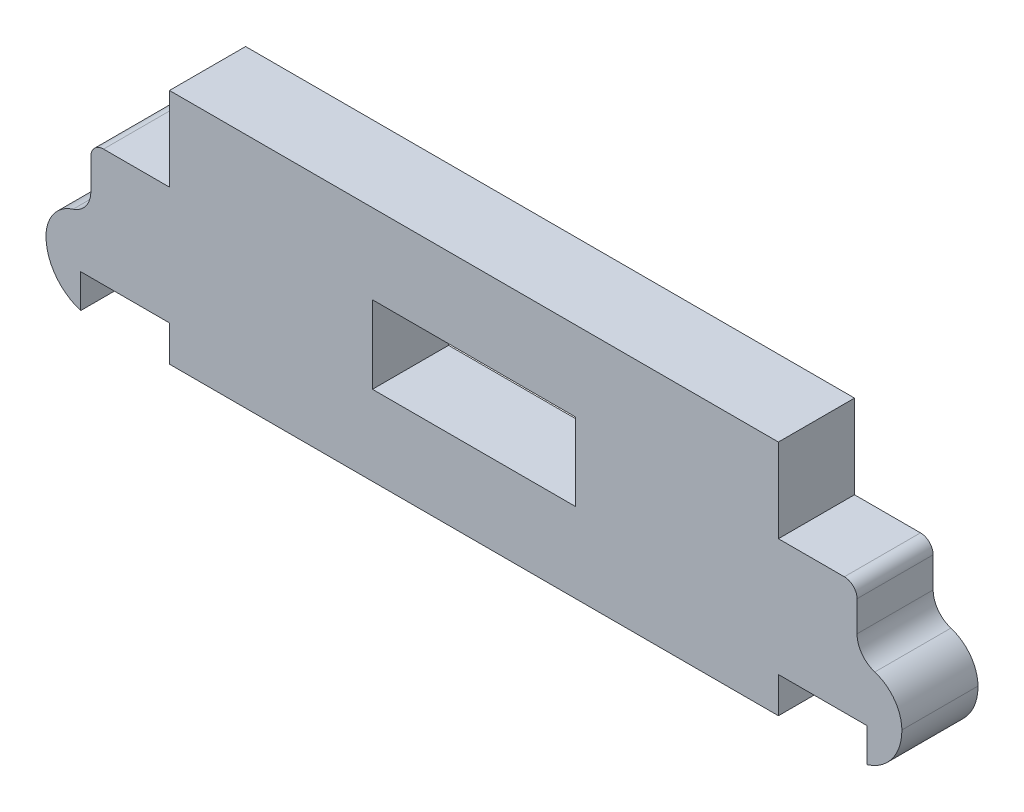
SolidWorks part; units mm, degrees
material "Balsa"
ref_plane "Front Plane" through (0, 0, 0) normal (0, 0, 1) x (1, 0, 0)
ref_plane "Top Plane" through (0, 0, 0) normal (0, 1, 0) x (1, 0, 0)
ref_plane "Right Plane" through (0, 0, 0) normal (1, 0, 0) x (0, 0, -1)
sketch "Sketch1" plane through (0, 0, 0) normal (0, 0, 1) x (1, 0, 0)
  line L0 (-10.0837, 0.2561) -> (13.9163, 9.5998) construction
  line L5 (-10.0837, 9.5998) -> (13.9163, 0.2561) construction
  line L6 (1.9163, 7.8907) -> (1.9163, -7.1327) construction
  line L8 (-2.0837, 3.3998) -> (5.9163, 3.3998)
  line L9 (-2.0837, 3.3998) -> (-2.0837, 6.4561)
  line L10 (-2.0837, 6.4561) -> (5.9163, 6.4561)
  line L11 (5.9163, 3.3998) -> (5.9163, 6.4561)
  line L12 (-2.0837, 3.3998) -> (5.9163, 6.4561) construction
  line L13 (-2.0837, 6.4561) -> (5.9163, 3.3998) construction
  line L19 (-10.0837, 9.5998) -> (-10.0837, 6.2998)
  line L20 (-10.0837, 6.2998) -> (-12.683, 6.2998)
  line L21 (-13.183, 5.7998) -> (-13.183, 4.6024)
  line L22 (-13.5837, 0.3353) -> (-13.5837, 1.6647)
  line L23 (-13.5837, 1.6647) -> (-10.0837, 1.6647)
  line L26 (-10.0837, 1.6647) -> (-10.0837, 0.2561)
  line L27 (13.9163, 1.6647) -> (13.9163, 0.2561)
  line L28 (17.4163, 1.6647) -> (13.9163, 1.6647)
  line L29 (17.4163, 0.3353) -> (17.4163, 1.6647)
  line L38 (-10.0837, 0.2561) -> (13.9163, 0.2561)
  line L45 (13.9163, 9.5998) -> (-10.0837, 9.5998)
  line L46 (17.0155, 5.7998) -> (17.0155, 4.6024)
  line L47 (13.9163, 6.2998) -> (16.5155, 6.2998)
  line L48 (13.9163, 9.5998) -> (13.9163, 6.2998)
  line L49 (-10.0837, 6.2998) -> (-10.0837, 1.6647) construction
  line L50 (13.9163, 6.2998) -> (13.9163, 1.6647) construction
  arc A4 (-12.683, 6.2998) -> (-13.183, 5.7998) centre (-12.683, 5.7998) ccw
  arc A5 (-13.183, 4.6024) -> (-13.8826, 3.6485) centre (-14.183, 4.6024) cw
  arc A6 (-13.8826, 3.6485) -> (-14.9504, 2.2037) centre (-13.4243, 2.1928) ccw
  arc A7 (-14.9504, 2.2037) -> (-13.5837, 0.3353) centre (-13.0087, 2.1899) ccw
  arc A8 (18.783, 2.2037) -> (17.4163, 0.3353) centre (16.8413, 2.1899) cw
  arc A9 (17.7152, 3.6485) -> (18.783, 2.2037) centre (17.2569, 2.1928) cw
  arc A10 (17.0155, 4.6024) -> (17.7152, 3.6485) centre (18.0155, 4.6024) ccw
  arc A11 (16.5155, 6.2998) -> (17.0155, 5.7998) centre (16.5155, 5.7998) cw
  point P12 (1.9163, 4.9279)
  dimension "D9" = 1.1974
  dimension "D11" = 1.5261
  dimension "D12" = 1.9417
  dimension "D13" = 1.1997
  dimension "D1" = 3.3
  dimension "D8" = 0.5
  dimension "D10" = 1
  dimension "D2" = 8
  dimension "D3" = 24
  dimension "D4" = 3.0563
  dimension "D5" = 4.6351
  dimension "D6" = 1.4086
  dimension "D7" = 2.5993
  dimension "D14" = 3.5
extrude "Boss-Extrude1" add sketch "Sketch1" along normal mid plane 3 contours L19 L20 A4 L21 A5 A6 A7 L22 L23 L26 L38 L27 L28 L29 A8 A9 A10 L46 A11 L47 L48 L45
